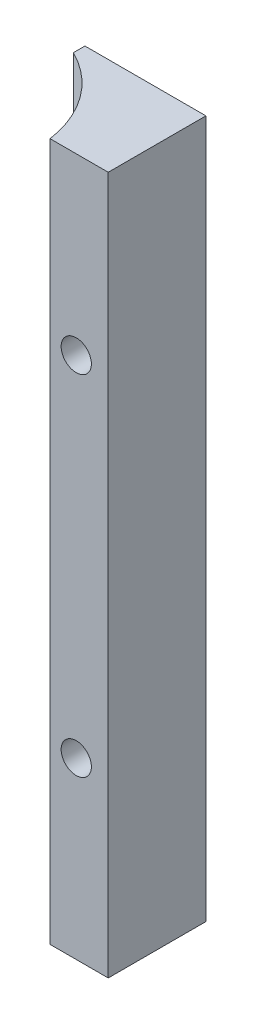
SolidWorks part; units mm, degrees
ref_plane "Front" through (0, 0, 0) normal (0, 0, 1) x (1, 0, 0)
ref_plane "Top" through (0, 0, 0) normal (0, 1, 0) x (1, 0, 0)
ref_plane "Right" through (0, 0, 0) normal (1, 0, 0) x (0, 0, -1)
sketch "Sketch1" plane through (0, 0, 0) normal (0, 1, 0) x (1, 0, 0)
  line L0 (0, 0) -> (0, 8.4)
  line L1 (0, 8.4) -> (-10.4025, 8.4)
  line L2 (-10.4025, 8.4) -> (-10.4025, 7.4)
  line L3 (-5, 0) -> (0, 0)
  arc A0 (-10.4025, 7.4) -> (-5, 0) centre (-14.7211, -1.425) cw
  dimension "D3" = 9.825
  dimension "D1" = 5
  dimension "D2" = 8.4
  dimension "D4" = 1.425
  dimension "D5" = 1
extrude "Boss-Extrude1" add sketch "Sketch1" along normal blind 60
sketch "Sketch2" plane through (0, 0, 0) normal (0, 0, 1) x (1, 0, 0)
  line L0 (-2.75, 60) -> (-2.75, 0) construction
  line L1 (-5, 60) -> (0, 60) construction
  line L2 (-5, 0) -> (0, 0) construction
  line L4 (-5, 60) -> (-5, 0) construction
  point P6 (-2.75, 45)
  point P7 (-2.75, 15)
  dimension "D1" = 15
  dimension "D2" = 15
  dimension "D3" = 2.25
hole_wizard "Ø2.6 (2.6) Diameter Hole1" positions "3DSketch1" profile "Sketch3" hole size "Ø2.6" standard "ANSI Metric" end condition up to next
sketch3d "3DSketch1"
  point P0 (-2.75, 45, 0)
  point P3 (-2.75, 15, 0)
sketch "Sketch3" plane through (-2.75, 45, 0) normal (1, 0, 0) x (0, -1, 0)
  line L0 (0, 0) -> (0, 8.4)
  line L1 (0, 8.4) -> (1.3, 8.4)
  line L2 (1.3, 8.4) -> (1.3, 0)
  line L5 (1.3, 0) -> (0, 0)
  line L11 (0, -6.35) -> (0, 107.95) construction
  dimension "Thru Hole Dia." = 2.6
  dimension "Thru Hole Depth" = 8.4
